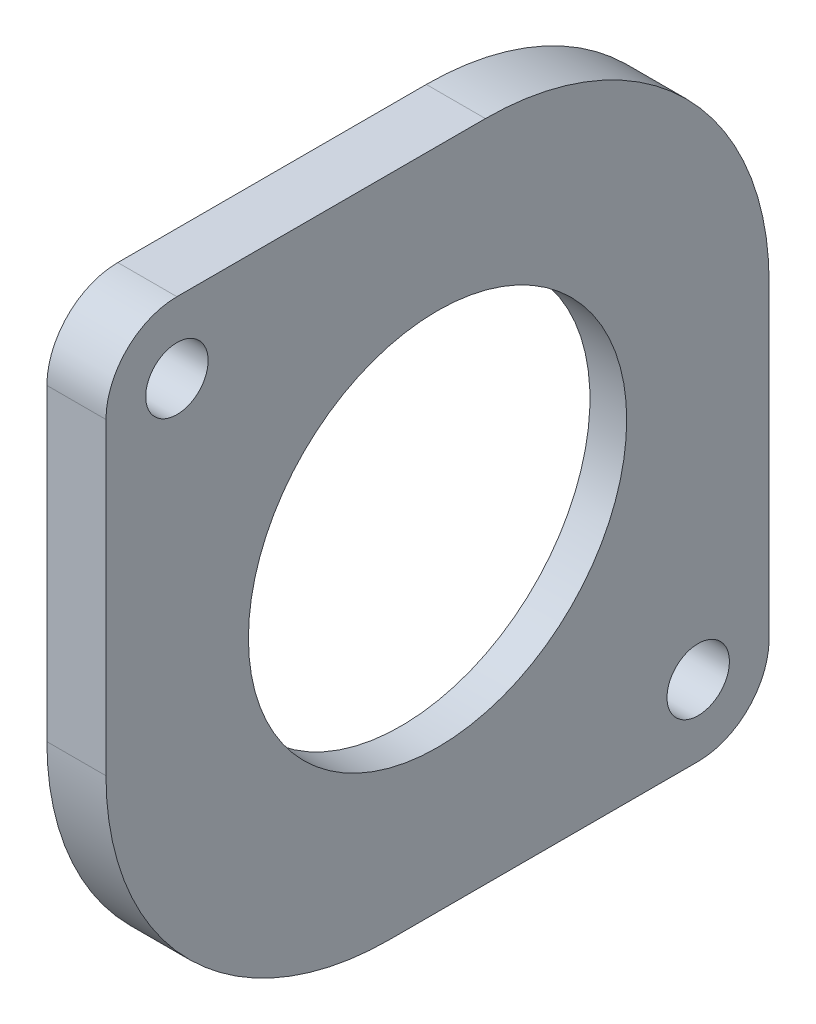
SolidWorks part; units mm, degrees
ref_plane "Front" through (0, 0, 0) normal (0, 0, 1) x (1, 0, 0)
ref_plane "Top" through (0, 0, 0) normal (0, 1, 0) x (1, 0, 0)
ref_plane "Right" through (0, 0, 0) normal (1, 0, 0) x (0, 0, -1)
sketch "Sketch1" plane through (0, 0, 0) normal (1, 0, 0) x (0, 0, -1)
  line L1 (-17.5, 22.2625) -> (3.2125, 22.2625)
  line L2 (-22.2625, 17.5) -> (-22.2625, -3.2125)
  line L3 (-3.2125, -22.2625) -> (17.5, -22.2625)
  line L4 (22.2625, 3.2125) -> (22.2625, -17.5)
  arc A0 (-17.5, 22.2625) -> (-22.2625, 17.5) centre (-17.5, 17.5) ccw
  arc A1 (17.5, -22.2625) -> (22.2625, -17.5) centre (17.5, -17.5) ccw
  circle A2 centre (-17.5, 17.5) radius 2.3479 construction
  circle A3 centre (17.5, -17.5) radius 2.3479 construction
  arc A4 (3.2125, 22.2625) -> (22.2625, 3.2125) centre (3.2125, 3.2125) cw
  arc A5 (-22.2625, -3.2125) -> (-3.2125, -22.2625) centre (-3.2125, -3.2125) ccw
  circle A6 centre (0, 0) radius 12.7
  dimension "D1" = 9.525
  dimension "D2" = 19.05
  dimension "D3" = 25.4
extrude "Boss-Extrude1" add sketch "Sketch1" along normal blind 3.9688
sketch "Sketch2" plane through (0, 0, 0) normal (-1, 0, 0) x (0, 0, 1)
  circle A0 centre (0, 0) radius 19.9974
  dimension "D1" = 39.9948
extrude "Cut-Extrude1" cut sketch "Sketch2" against normal blind 1.5011
hole_wizard "#8 Clearance Hole1" positions "Sketch4" profile "Sketch5" hole size "#8" standard "ANSI Inch" end condition through all
sketch "Sketch4" plane through (3.9688, 0, 0) normal (1, 0, 0) x (0, 0, -1)
  arc A0 (-17.5, 22.2625) -> (-22.2625, 17.5) centre (-17.5, 17.5) ccw construction
  arc A1 (17.5, -22.2625) -> (22.2625, -17.5) centre (17.5, -17.5) ccw construction
  point P0 (-17.5, 17.5)
  point P2 (17.5, -17.5)
  point P5 (0, 0)
  point P9 (0, 0)
sketch "Sketch5" plane through (3.9688, 17.5, 17.5) normal (0, 1, 0) x (0, 0, -1)
  line L0 (0, 0) -> (0, 3.9688)
  line L1 (0, 3.9688) -> (2.0955, 3.9688)
  line L2 (2.0955, 3.9688) -> (2.0955, 0)
  line L5 (2.0955, 0) -> (0, 0)
  line L11 (0, -6.35) -> (0, 107.95) construction
  dimension "Thru Hole Dia." = 4.191
  dimension "Thru Hole Depth" = 3.9688
fillet "Fillet1" radius 0.3969 1 edges at (0, 0, 19.9974)
